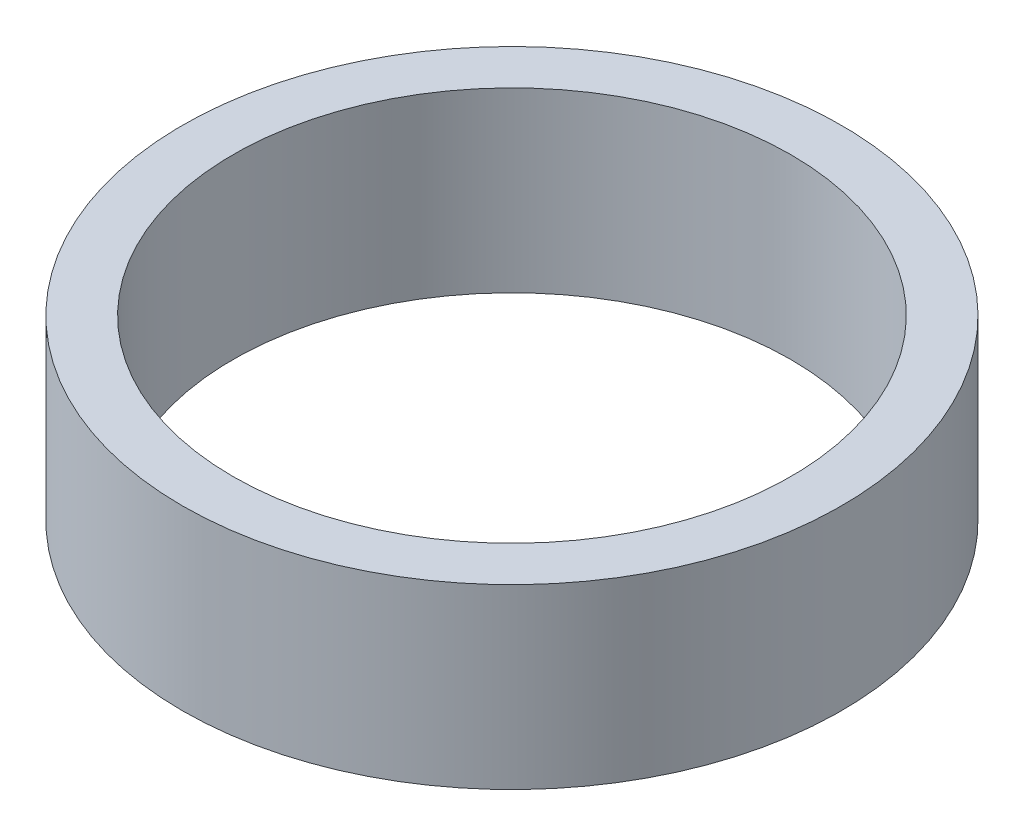
SolidWorks part; units mm, degrees
ref_plane "Front Plane" through (0, 0, 0) normal (0, 0, 1) x (1, 0, 0)
ref_plane "Top Plane" through (0, 0, 0) normal (0, 1, 0) x (1, 0, 0)
ref_plane "Right Plane" through (0, 0, 0) normal (1, 0, 0) x (0, 0, -1)
sketch "Sketch1" plane through (0, 0, 0) normal (0, 1, 0) x (1, 0, 0)
  circle A0 centre (0, 0) radius 11
  circle A2 centre (0, 0) radius 13
  dimension "D1" = 22
  dimension "D2" = 2
extrude "Boss-Extrude1" add sketch "Sketch1" along normal blind 7
